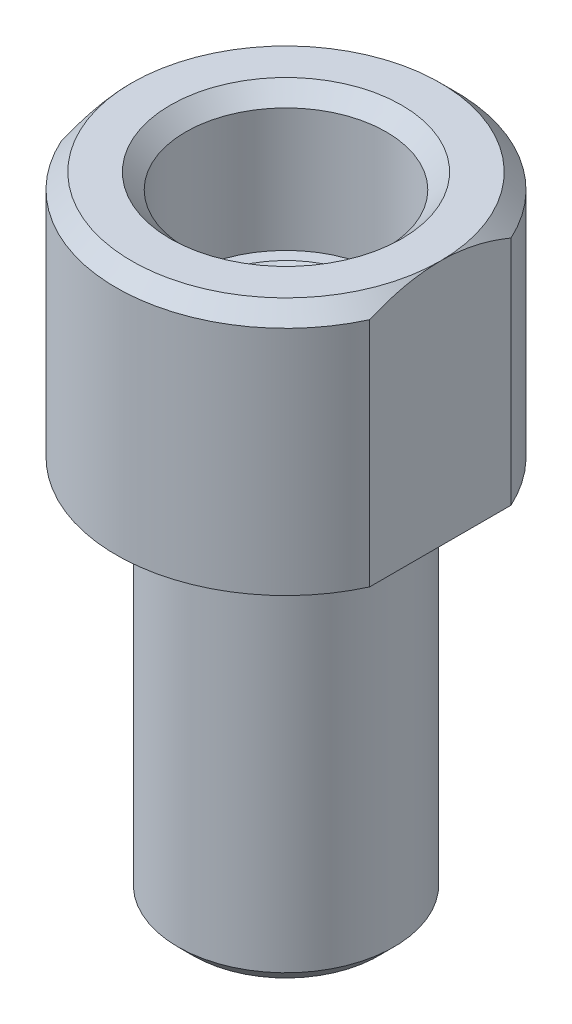
SolidWorks part; units mm, degrees
ref_plane "Plan de face" through (0, 0, 0) normal (0, 0, 1) x (1, 0, 0)
ref_plane "Plan de dessus" through (0, 0, 0) normal (0, 1, 0) x (1, 0, 0)
ref_plane "Plan de droite" through (0, 0, 0) normal (1, 0, 0) x (0, 0, -1)
sketch "Esquisse1" plane through (0, 0, 0) normal (0, 0, 1) x (1, 0, 0)
  line L0 (0, 0) -> (0, 29.7361) construction
  line L1 (4.8, 0) -> (4.8, 10)
  line L2 (4, 10) -> (4, 26)
  line L3 (4, 26) -> (5.2, 26)
  line L4 (5.2, 26) -> (5.2, 32)
  line L5 (5.2, 32) -> (6.5, 32)
  line L6 (6.5, 32) -> (6.5, 41)
  line L7 (6.5, 41) -> (11, 41)
  line L8 (11, 41) -> (11, 25)
  line L9 (11, 25) -> (9.55, 25)
  line L10 (9.55, 25) -> (9.55, 26.13)
  line L11 (9.55, 26.13) -> (7.55, 26.13)
  line L12 (7.55, 26.13) -> (7.55, 25)
  line L13 (7.55, 25) -> (7, 25)
  line L14 (7, 25) -> (7, 0)
  line L15 (7, 0) -> (4.8, 0)
  line L16 (4.8, 10) -> (4, 10)
  line L17 (4.8, 10) -> (4, 10)
  dimension "D1" = 25
  dimension "D2" = 16
  dimension "D3" = 9.55
  dimension "D4" = 11
  dimension "D5" = 7.55
  dimension "D6" = 5.2
  dimension "7" = 7
  dimension "D7" = 4.8
  dimension "D8" = 6.5
  dimension "D9" = 9
  dimension "D10" = 15
  dimension "D11" = 31
  dimension "D12" = 4
  dimension "D13" = 1.13
revolve "Révolution1" add sketch "Esquisse1" angle 360 about L0
chamfer "Chanfrein3" distance 1 angle 45 1 edges at (0, 41, -11)
sketch "Esquisse2" plane through (0, 41, 0) normal (0, 1, 0) x (1, 0, 0)
  line L0 (0, 0) -> (0, 11) construction
  line L1 (-10, 4.5826) -> (-10, -4.5826)
  line L2 (10, 4.5826) -> (10, -4.5826)
  circle A0 centre (0, 0) radius 11 construction
  arc A1 (-10, 4.5826) -> (-10, -4.5826) centre (0, 0) ccw
  arc A2 (10, 4.5826) -> (10, -4.5826) centre (0, 0) cw
  dimension "D1" = 20
extrude "Enlèv. mat.-Extru.1" cut sketch "Esquisse2" against normal through all
chamfer "Chanfrein1" distance 1 angle 45 2 edges at (0, 41, -6.5) (0, 0, -7)
chamfer "Chanfrein2" distance 0.5 angle 45 4 edges at (0, 0, -4.8) (0, 10, -4) (0, 26, -4) (0, 32, -5.2)
equation "\"D\"= 7 - 0.3"
